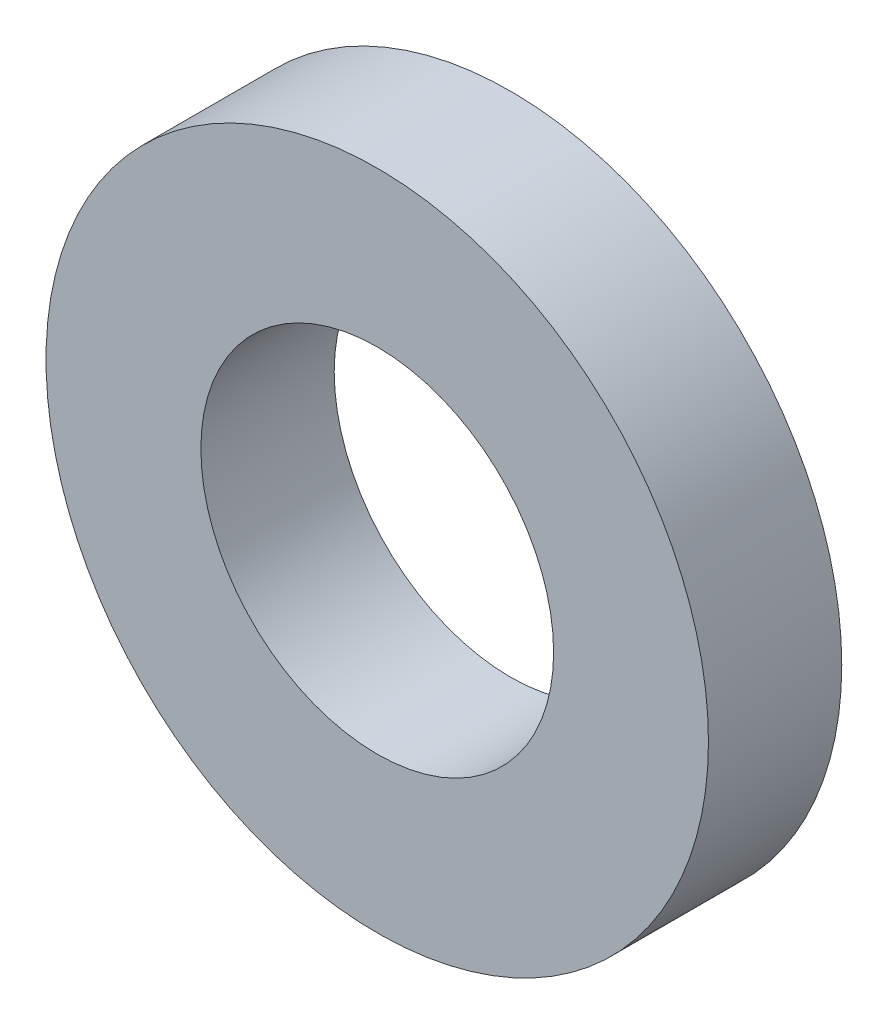
SolidWorks part; units mm, degrees
ref_plane "Piano frontale" through (0, 0, 0) normal (0, 0, 1) x (1, 0, 0)
ref_plane "Piano superiore" through (0, 0, 0) normal (0, 1, 0) x (1, 0, 0)
ref_plane "Piano destro" through (0, 0, 0) normal (1, 0, 0) x (0, 0, -1)
sketch "Schizzo1" plane through (0, 0, 0) normal (0, 0, 1) x (1, 0, 0)
  circle A0 centre (0, 0) radius 11.925
  dimension "D1" = 23.85
extrude "Estrusione-Estrusione1" add sketch "Schizzo1" along normal blind 4.8
hole_wizard "Foro Ø25.5 (12.7)-1" positions "Schizzo2" profile "Schizzo3" hole size "Ø25.5" standard "ISO" end condition through all
sketch "Schizzo2" plane through (0, 0, 4.8) normal (0, 0, 1) x (1, 0, 0)
  point P0 (0, 0)
sketch "Schizzo3" plane through (0, 0, 4.8) normal (1, 0, 0) x (0, -1, 0)
  line L0 (0, 0) -> (0, 4.8)
  line L1 (0, 4.8) -> (6.35, 4.8)
  line L2 (6.35, 4.8) -> (6.35, 0)
  line L5 (6.35, 0) -> (0, 0)
  line L11 (0, -6.35) -> (0, 107.95) construction
  dimension "Thru Hole Dia." = 12.7
  dimension "Thru Hole Depth" = 4.8
